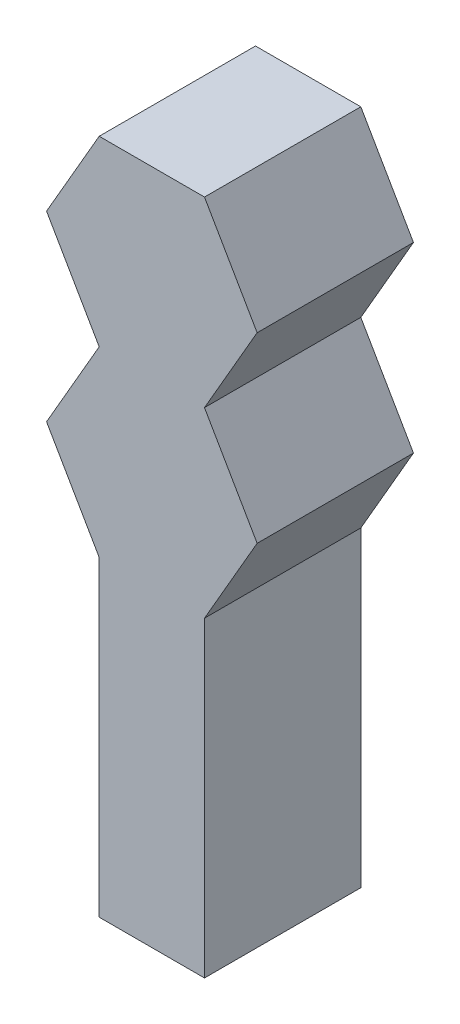
SolidWorks part; units mm, degrees
ref_plane "Front Plane" through (0, 0, 0) normal (0, 0, 1) x (1, 0, 0)
ref_plane "Top Plane" through (0, 0, 0) normal (0, 1, 0) x (1, 0, 0)
ref_plane "Right Plane" through (0, 0, 0) normal (1, 0, 0) x (0, 0, -1)
sketch "Sketch1" plane through (0, 0, 0) normal (0, 0, 1) x (1, 0, 0)
  line L1 (0, 0) -> (2.0207, 0)
  line L2 (0, 0) -> (0, 5.98)
  line L4 (2.0207, 0) -> (2.0207, 5.98)
  line L5 (3.0311, 7.73) -> (2.0207, 9.48)
  line L7 (0, 9.48) -> (-1.0104, 7.73)
  line L8 (-1.0104, 7.73) -> (0, 5.98)
  line L10 (2.0207, 5.98) -> (3.0311, 7.73)
  line L11 (3.0311, 11.23) -> (2.0207, 12.98)
  line L12 (2.0207, 12.98) -> (0, 12.98)
  line L13 (0, 12.98) -> (-1.0104, 11.23)
  line L14 (-1.0104, 11.23) -> (0, 9.48)
  line L16 (2.0207, 9.48) -> (3.0311, 11.23)
  line L17 (2.0207, 9.48) -> (1.0104, 9.48) [skipped]
  line L18 (1.0104, 9.48) -> (2.0207, 9.48) [skipped]
  line L19 (0, 5.98) -> (1.0104, 5.98) [skipped]
  circle A0 centre (1.0104, 7.73) radius 1.75 construction
  circle A1 centre (1.0104, 11.23) radius 1.75 construction
  point P1 (0, 0)
  point P14 (1.0515, 8.1175)
  point P22 (4.7571, 13.2564)
  point P23 (1.0114, 7.7346)
  point P24 (1.0112, 7.7293)
  point P25 (1.0112, 11.7028)
  point P26 (1.0112, 11.2196)
  point P27 (0, 0)
  dimension "D1" = 2.0207
  dimension "D2" = 5.98
  dimension "D4" = 2.0207
extrude "Boss-Extrude1" add sketch "Sketch1" along normal blind 3
sketch "Sketch2" plane through (0, 0, 3) normal (0, 0, 1) x (1, 0, 0)
  line L1 (2.3685, 11.1721) -> (1.7046, 12.3221)
  line L2 (1.7046, 12.3221) -> (0.3767, 12.3221)
  line L3 (0.3767, 12.3221) -> (-0.2873, 11.1721)
  line L4 (-0.2873, 11.1721) -> (0.3767, 10.0221)
  line L5 (0.3767, 10.0221) -> (1.7046, 10.0221)
  line L6 (1.7046, 10.0221) -> (2.3685, 11.1721)
  line L7 (2.3685, 7.7748) -> (1.7046, 8.9248)
  line L8 (1.7046, 8.9248) -> (0.3767, 8.9248)
  line L9 (0.3767, 8.9248) -> (-0.2873, 7.7748)
  line L10 (-0.2873, 7.7748) -> (0.3767, 6.6248)
  line L11 (0.3767, 6.6248) -> (1.7046, 6.6248)
  line L12 (1.7046, 6.6248) -> (2.3685, 7.7748)
  circle A0 centre (1.0406, 11.1721) radius 1.15 construction
  circle A1 centre (1.0406, 7.7748) radius 1.15 construction
  point P9 (1.0406, 7.7748)
  point P17 (1.0406, 11.1721)
  dimension "D1" = 2.6558
  dimension "D2" = 2.6558
